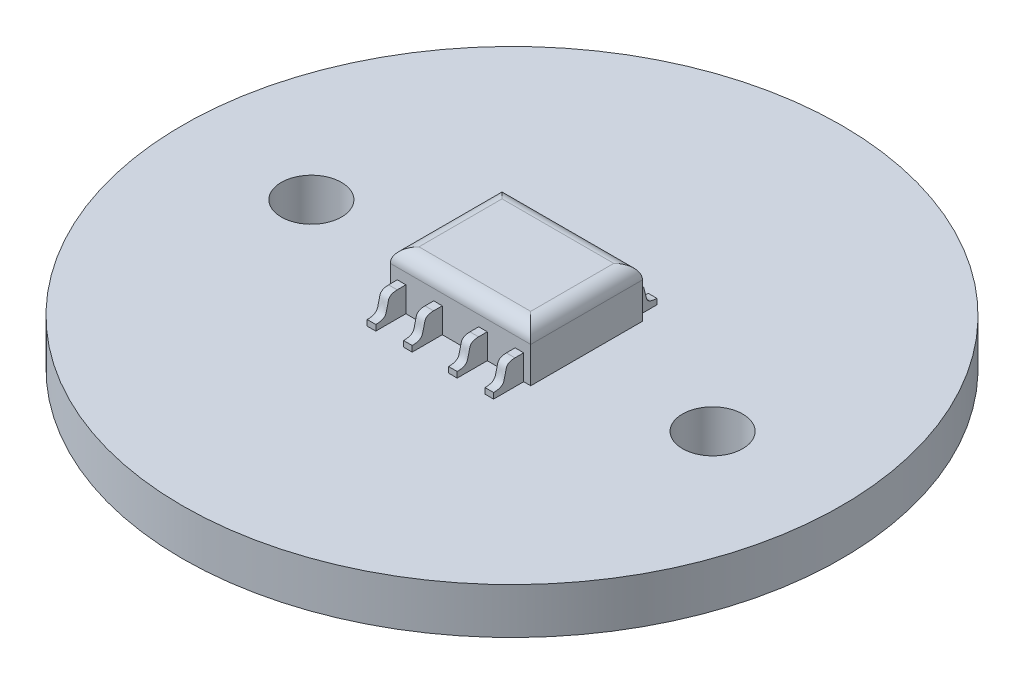
SolidWorks part; units mm, degrees
ref_plane "Front Plane" through (0, 0, 0) normal (0, 0, 1) x (1, 0, 0)
ref_plane "Top Plane" through (0, 0, 0) normal (0, 1, 0) x (1, 0, 0)
ref_plane "Right Plane" through (0, 0, 0) normal (1, 0, 0) x (0, 0, -1)
sketch "Sketch1" plane through (0, 0, 0) normal (0, 1, 0) x (1, 0, 0)
  circle A0 centre (0, 0) radius 11.5
  circle A1 centre (0, 0) radius 7 construction
  circle A2 centre (-7, 0) radius 1.05
  circle A3 centre (7, 0) radius 1.05
  dimension "D1" = 23
  dimension "D2" = 14
  dimension "D3" = 2.1
extrude "Boss-Extrude1" add sketch "Sketch1" along normal blind 1.6
sketch "Sketch2" plane through (0, 1.6, 0) normal (0, 1, 0) x (1, 0, 0)
  line L0 (0, -0.88) -> (0, 0.88) construction
  line L1 (-2.45, 2.1028) -> (2.45, 2.1028)
  line L2 (-2.45, 2.1028) -> (-2.45, -1.7972)
  line L3 (-2.45, -1.7972) -> (2.45, -1.7972)
  line L4 (2.45, 2.1028) -> (2.45, -1.7972)
  line L5 (-2.45, 2.1028) -> (2.45, -1.7972) construction
  line L6 (-2.45, -1.7972) -> (2.45, 2.1028) construction
  point P0 (0, 0.1528)
  dimension "D1" = 4.9
  dimension "D2" = 3.9
extrude "Boss-Extrude2" add sketch "Sketch2" along normal blind 1.75
sketch "Sketch3" plane through (0, 1.6, 0) normal (0, 1, 0) x (1, 0, 0)
  line L0 (-2.45, -1.7972) -> (2.45, -1.7972) construction
  line L1 (-2.205, -1.7972) -> (-1.905, -1.7972)
  line L2 (-2.205, -1.7972) -> (-2.205, -2.8472)
  line L3 (-2.205, -2.8472) -> (-1.905, -2.8472)
  line L4 (-1.905, -1.7972) -> (-1.905, -2.8472)
  line L5 (0, -1.8425) -> (0, 1.8425) construction
  line L6 (-0.935, -1.7972) -> (-0.635, -1.7972)
  line L7 (-0.935, -1.7972) -> (-0.935, -2.8472)
  line L8 (-0.935, -2.8472) -> (-0.635, -2.8472)
  line L9 (-0.635, -1.7972) -> (-0.635, -2.8472)
  point P10 (-2.055, -2.8472)
  point P11 (-0.785, -2.8472)
  dimension "D1" = 1.05
  dimension "D2" = 1.27
  dimension "D3" = 0.3
  dimension "D4" = 0.635
extrude "Boss-Extrude3" add sketch "Sketch3" along normal blind 0.875
mirror "Mirror1" about plane through (0, 0, 0) normal (1, 0, 0) of "Boss-Extrude3"
mirror "Mirror2" about plane through (0, 0, 0) normal (0, 0, 1) of "Mirror1", "Boss-Extrude3"
fillet "Fillet1" radius 0.5 4 edges at (0, 3.35, 1.7972) (-2.45, 3.35, -0.1528) (0, 3.35, -2.1028) (2.45, 3.35, -0.1528)
sketch "Sketch4" plane through (2.205, 0, 0) normal (1, 0, 0) x (0, 0, -1)
  line L1 (2.8472, 2.475) -> (2.8472, 1.6) construction
  line L5 (2.1028, 2.475) -> (2.8472, 2.475)
  line L6 (2.8472, 2.475) -> (2.8472, 1.8)
  spline S0 degree 3 poles (2.1028, 2.475) (2.2656, 2.4691) (2.3432, 2.4188) (2.4182, 2.3158) (2.4324, 2.178) (2.5138, 1.8708) (2.6481, 1.8006) (2.8472, 1.8) knots 0 0 0 0 0.320657 0.400503 0.754238 0.818609 1 1 1 1
extrude "Cut-Extrude1" cut sketch "Sketch4" against normal through all both and the other way through all
mirror "Mirror3" about plane through (0, 0, 0) normal (0, 0, 1) of "Cut-Extrude1"
